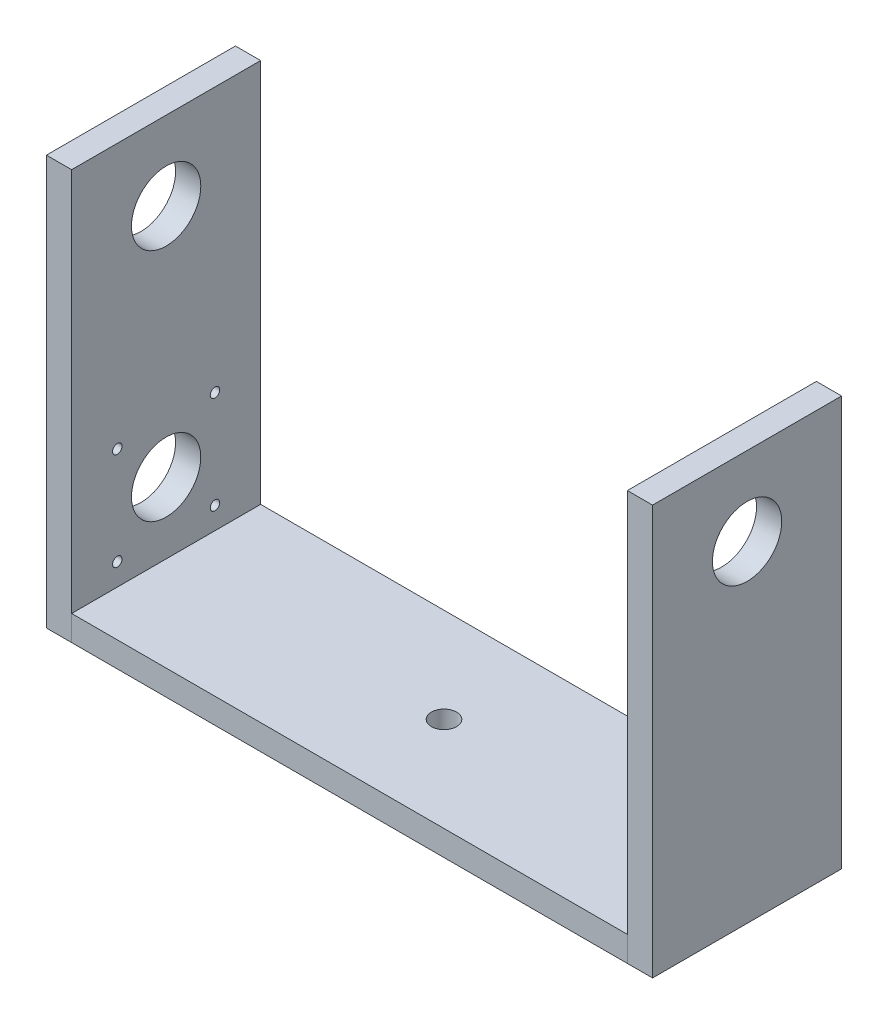
SolidWorks part; units mm, degrees
ref_plane "Front Plane" through (0, 0, 0) normal (0, 0, 1) x (1, 0, 0)
ref_plane "Top Plane" through (0, 0, 0) normal (0, 1, 0) x (1, 0, 0)
ref_plane "Right Plane" through (0, 0, 0) normal (1, 0, 0) x (0, 0, -1)
sketch "Sketch1" plane through (0, 0, 0) normal (0, 0, 1) x (1, 0, 0)
  line L1 (-88.2, -4) -> (88.2, -4)
  line L2 (-88.2, -4) -> (-88.2, 4)
  line L3 (-88.2, 4) -> (88.2, 4)
  line L4 (88.2, -4) -> (88.2, 4)
  line L5 (-88.2, -4) -> (88.2, 4) construction
  line L6 (-88.2, 4) -> (88.2, -4) construction
  point P0 (0, 0)
  dimension "D1" = 8
  dimension "D2" = 176.4
extrude "Boss-Extrude1" add sketch "Sketch1" along normal blind 60
sketch "Sketch2" plane through (88.2, 0, 0) normal (1, 0, 0) x (0, 0, -1)
  line L1 (-60, -4) -> (0, -4)
  line L2 (-60, -4) -> (-60, 126)
  line L3 (-60, 126) -> (0, 126)
  line L4 (0, -4) -> (0, 126)
  dimension "D1" = 130
extrude "Boss-Extrude2" add sketch "Sketch2" along normal blind 8 separate body
sketch "Sketch3" plane through (-88.2, 0, 0) normal (-1, 0, 0) x (0, 0, 1)
  line L4 (60, -4) -> (60, 126)
  line L5 (0, -4) -> (60, -4)
  line L6 (0, 126) -> (0, -4)
  line L7 (60, 126) -> (0, 126)
  line L8 (60, -4) -> (60, 126)
  line L9 (0, -4) -> (60, -4)
  line L10 (0, 126) -> (0, -4)
  line L11 (60, 126) -> (0, 126)
  dimension "D1" = 0
extrude "Boss-Extrude3" add sketch "Sketch3" along normal blind 8 separate body
sketch "Sketch4" plane through (96.2, 0, 0) normal (1, 0, 0) x (0, 0, -1)
  line L0 (0, 126) -> (-60, 126) construction
  circle A0 centre (-30, 101) radius 11
  dimension "D1" = 22
  dimension "D2" = 30
  dimension "D3" = 25
extrude "Cut-Extrude1" cut sketch "Sketch4" against normal through all
sketch "Sketch5" plane through (0, -4, 0) normal (0, -1, 0) x (1, 0, 0)
  circle A0 centre (0, 30) radius 4
  dimension "D1" = 8
  dimension "D2" = 30
extrude "Cut-Extrude2" cut sketch "Sketch5" against normal up to next (8 mm away)
sketch "Sketch6" plane through (-96.2, 0, 0) normal (-1, 0, 0) x (0, 0, 1)
  line L0 (60, -4) -> (60, 126) construction
  line L1 (14.5, 11) -> (45.5, 11) construction
  line L2 (14.5, 11) -> (14.5, 42) construction
  line L3 (14.5, 42) -> (45.5, 42) construction
  line L4 (45.5, 11) -> (45.5, 42) construction
  line L5 (14.5, 11) -> (45.5, 42) construction
  line L6 (14.5, 42) -> (45.5, 11) construction
  line L7 (55, -4) -> (5, -4) construction
  circle A0 centre (14.5, 42) radius 1.5
  circle A1 centre (45.5, 42) radius 1.5
  circle A2 centre (45.5, 11) radius 1.5
  circle A3 centre (14.5, 11) radius 1.5
  circle A4 centre (30, 26.5) radius 11
  point P0 (30, 26.5)
  dimension "D5" = 3
  dimension "D6" = 3
  dimension "D7" = 3
  dimension "D8" = 3
  dimension "D9" = 22
  dimension "D1" = 31
  dimension "D2" = 31
  dimension "D3" = 30
  dimension "D4" = 15
extrude "Cut-Extrude3" cut sketch "Sketch6" against normal up to next (8 mm away)
